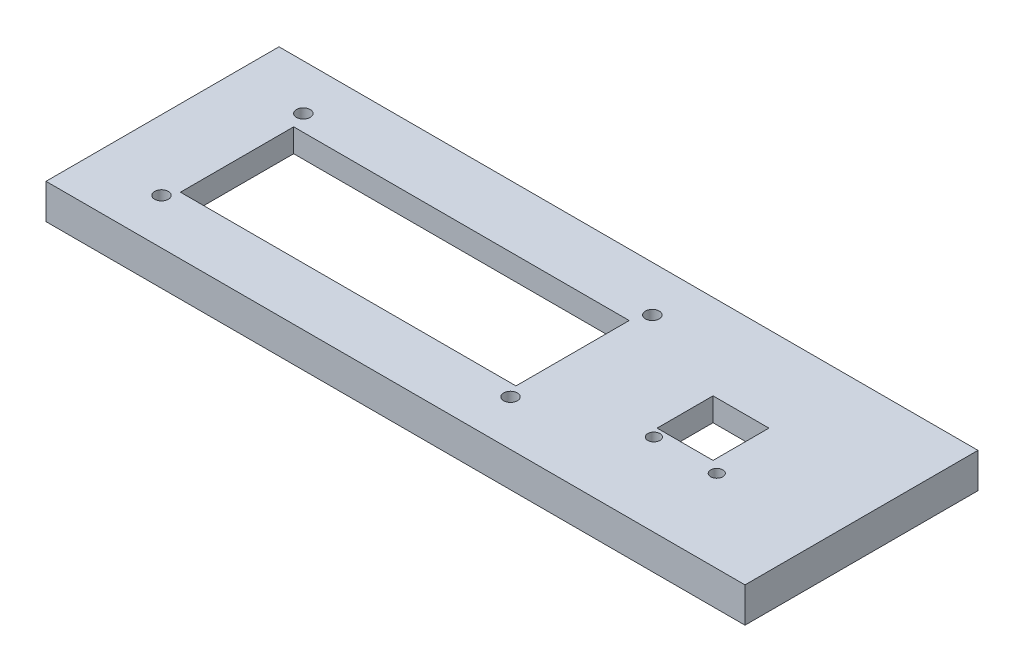
SolidWorks part; units mm, degrees
ref_plane "Front Plane" through (0, 0, 0) normal (0, 0, 1) x (1, 0, 0)
ref_plane "Top Plane" through (0, 0, 0) normal (0, 1, 0) x (1, 0, 0)
ref_plane "Right Plane" through (0, 0, 0) normal (1, 0, 0) x (0, 0, -1)
sketch "Sketch2" plane through (0, 0, 0) normal (0, 1, 0) x (1, 0, 0)
  line L1 (0, 0) -> (150, 0)
  line L2 (0, 0) -> (0, 50)
  line L3 (0, 50) -> (150, 50)
  line L4 (150, 0) -> (150, 50)
  dimension "D1" = 150
  dimension "D2" = 50
extrude "Boss-Extrude1" add sketch "Sketch2" along normal blind 7.5
sketch "Sketch3" plane through (0, 7.5, 0) normal (0, 1, 0) x (1, 0, 0)
  line L0 (15, 9.7837) -> (89.9, 9.7837) construction
  line L1 (15, 9.7837) -> (89.9, 9.7837) construction
  line L2 (15, 9.7837) -> (15, 40.2163) construction
  line L3 (15, 40.2163) -> (89.9, 40.2163) construction
  line L4 (89.9, 9.7837) -> (89.9, 40.2163) construction
  line L5 (15, 9.7837) -> (15, 40.2163) construction
  line L7 (13.525, 40.2163) -> (16.475, 40.2163) construction
  line L8 (-17.5953, 42.8554) -> (-14.6453, 42.8554) construction
  line L9 (75, 0) -> (75, 50) construction
  line L10 (0, 0) -> (150, 0) construction
  line L11 (150, 50) -> (0, 50) construction
  line L12 (150, 25) -> (0, 25) construction
  line L13 (150, 0) -> (150, 50) construction
  line L14 (0, 50) -> (0, 0) construction
  circle A0 centre (15, 40.2163) radius 1.475
  circle A1 centre (89.9, 40.2163) radius 1.475
  circle A2 centre (89.9, 9.7837) radius 1.475
  circle A3 centre (15, 9.7837) radius 1.475
  dimension "D1" = 15
extrude "Cut-Extrude1" cut sketch "Sketch3" against normal through all
sketch "Sketch4" plane through (0, 7.5, 0) normal (0, 1, 0) x (1, 0, 0)
  line L0 (107.2384, 34.5) -> (107.2384, 15.5) construction
  line L1 (107.45, 34.5) -> (133.85, 34.5)
  line L2 (107.45, 34.5) -> (107.45, 15.5) construction
  line L3 (107.45, 15.5) -> (133.85, 15.5)
  line L4 (133.85, 34.5) -> (133.85, 15.5) construction
  line L5 (112.7384, 17.7) -> (126.2384, 17.7) construction
  line L6 (107.2384, 15.5) -> (133.6384, 15.5) construction
  line L7 (112.7384, 17.7) -> (126.2384, 17.7) construction
  line L8 (126.2384, 17.7) -> (126.2384, 15.5) construction
  line L9 (126.2384, 17.7) -> (126.2384, 15.5) construction
  line L10 (150, 25) -> (0, 25) construction
  line L11 (150, 0) -> (150, 50) construction
  line L12 (0, 50) -> (0, 0) construction
  line L13 (92.45, 7) -> (92.45, 43) construction
  circle A0 centre (112.7384, 17.7) radius 1.3
  circle A1 centre (126.2384, 17.7) radius 1.3
  circle A2 centre (112.7384, 17.7) radius 1.3 construction
  dimension "D1" = 15
extrude "Cut-Extrude2" cut sketch "Sketch4" against normal through all contours A0 | A1
sketch "Sketch6" plane through (0, 0, 0) normal (0, -1, 0) x (1, 0, 0)
  line L17 (145, -45) -> (145, -5)
  line L18 (5, -45) -> (145, -45)
  line L19 (5, -5) -> (5, -45)
  line L20 (145, -5) -> (5, -5)
  line L21 (145, -45) -> (145, -5)
  line L22 (5, -45) -> (145, -45)
  line L23 (5, -5) -> (5, -45)
  line L24 (145, -5) -> (5, -5)
  dimension "D1" = 5
extrude "Cut-Extrude3" cut sketch "Sketch6" against normal offset from surface (2.5 mm away) 5 up to face at (112.7384, 7.5, -16.4)
sketch "Sketch8" plane through (0, 7.5, 0) normal (0, 1, 0) x (1, 0, 0)
  line L1 (16.45, 36.7) -> (88.45, 36.7)
  line L2 (16.45, 36.7) -> (16.45, 12.4)
  line L3 (16.45, 12.4) -> (88.45, 12.4)
  line L4 (88.45, 36.7) -> (88.45, 12.4)
extrude "Cut-Extrude4" cut sketch "Sketch8" against normal through all
sketch "Sketch9" plane through (0, 7.5, 0) normal (0, 1, 0) x (1, 0, 0)
  line L1 (111.4384, 31.7) -> (123.4384, 31.7)
  line L2 (111.4384, 31.7) -> (111.4384, 19.7)
  line L3 (111.4384, 19.7) -> (123.4384, 19.7)
  line L4 (123.4384, 31.7) -> (123.4384, 19.7)
extrude "Cut-Extrude5" cut sketch "Sketch9" against normal through all
